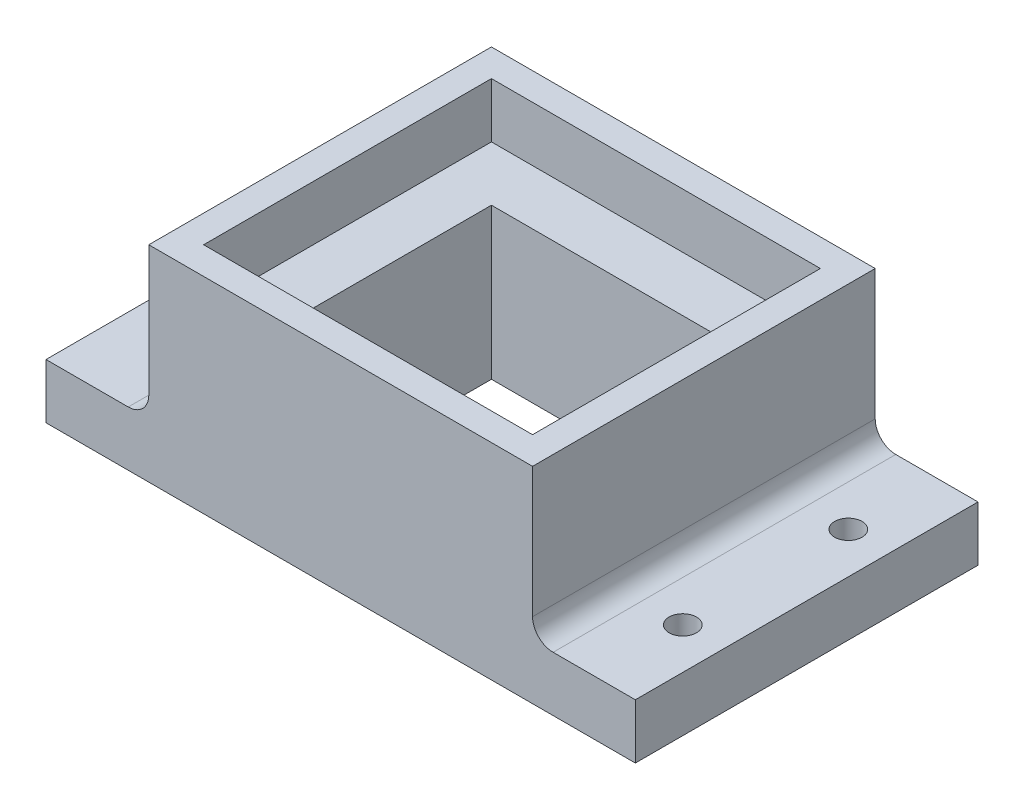
SolidWorks part; units mm, degrees
ref_plane "Front Plane" through (0, 0, 0) normal (0, 0, 1) x (1, 0, 0)
ref_plane "Top Plane" through (0, 0, 0) normal (0, 1, 0) x (1, 0, 0)
ref_plane "Right Plane" through (0, 0, 0) normal (1, 0, 0) x (0, 0, -1)
sketch "Sketch1" plane through (0, 0, 0) normal (0, 1, 0) x (1, 0, 0)
  line L1 (-28, -25) -> (28, -25)
  line L2 (-28, -25) -> (-28, 25)
  line L3 (-28, 25) -> (28, 25)
  line L4 (28, -25) -> (28, 25)
  line L5 (-28, -25) -> (28, 25) construction
  line L6 (-28, 25) -> (28, -25) construction
  point P0 (0, 0)
  dimension "D1" = 50
  dimension "D2" = 56
extrude "Boss-Extrude1" add sketch "Sketch1" along normal blind 30
sketch "Sketch3" plane through (0, 30, 0) normal (0, 1, 0) x (1, 0, 0)
  line L0 (28, 25) -> (-28, 25) construction
  line L1 (-24, -21) -> (24, -21)
  line L2 (-24, -21) -> (-24, 21)
  line L3 (-24, 21) -> (24, 21)
  line L4 (24, -21) -> (24, 21)
  line L5 (-24, -21) -> (24, 21) construction
  line L6 (-24, 21) -> (24, -21) construction
  line L7 (28, -25) -> (28, 25) construction
  point P0 (0, 0)
  dimension "D1" = 4
  dimension "D2" = 4
extrude "Cut-Extrude1" cut sketch "Sketch3" against normal blind 8
sketch "Sketch4" plane through (0, 0, 25) normal (0, 0, 1) x (1, 0, 0)
  line L1 (-28, 0) -> (-43, 0)
  line L2 (-28, 0) -> (-28, 8)
  line L3 (-28, 8) -> (-43, 8)
  line L4 (-43, 0) -> (-43, 8)
  line L5 (28, 0) -> (43, 0)
  line L6 (28, 0) -> (28, 8)
  line L7 (28, 8) -> (43, 8)
  line L8 (43, 0) -> (43, 8)
  dimension "D1" = 8
  dimension "D2" = 15
extrude "Boss-Extrude2" add sketch "Sketch4" against normal up to surface (50 mm away) up to face at (0, 15, -25)
fillet "Fillet1" radius 3 2 edges at (28, 8, 0) (-28, 8, 0)
sketch "Sketch5" plane through (0, 22, 0) normal (0, 1, 0) x (1, 0, 0)
  line L0 (-24, 21) -> (-24, -21) construction
  line L1 (-16, -13) -> (16, -13)
  line L2 (-16, -13) -> (-16, 13)
  line L3 (-16, 13) -> (16, 13)
  line L4 (16, -13) -> (16, 13)
  line L5 (-16, -13) -> (16, 13) construction
  line L6 (-16, 13) -> (16, -13) construction
  line L7 (24, 21) -> (-24, 21) construction
  point P0 (0, 0)
  dimension "D1" = 8
  dimension "D2" = 8
extrude "Cut-Extrude2" cut sketch "Sketch5" against normal through all both and the other way through all
sketch "Sketch6" plane through (0, 8, 0) normal (0, 1, 0) x (1, 0, 0)
  line L0 (-37, 25) -> (-37, -25) construction
  line L1 (-43, 25) -> (-31, 25) construction
  line L2 (-31, -25) -> (-43, -25) construction
  line L3 (-37, -12.0794) -> (-37, -25) construction
  line L4 (-37, 12.0794) -> (-37, 25) construction
  line L5 (0, 13) -> (0, -13) construction
  line L6 (-16, 13) -> (16, 13) construction
  line L7 (16, -13) -> (-16, -13) construction
  circle A0 centre (-37, 12.0794) radius 2
  circle A1 centre (-37, -12.0794) radius 2
  circle A2 centre (37, -12.0794) radius 2
  circle A3 centre (37, 12.0794) radius 2
  dimension "D1" = 4
  dimension "D2" = 4
  dimension "D3" = 12.9206
extrude "Cut-Extrude3" cut sketch "Sketch6" against normal through all both
